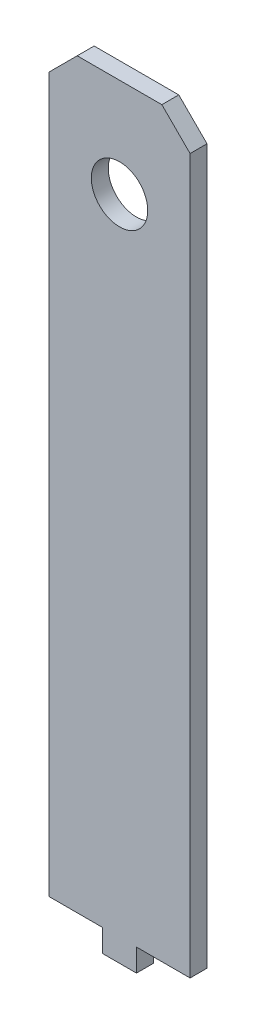
SolidWorks part; units mm, degrees
ref_plane "Front Plane" through (0, 0, 0) normal (0, 0, 1) x (1, 0, 0)
ref_plane "Top Plane" through (0, 0, 0) normal (0, 1, 0) x (1, 0, 0)
ref_plane "Right Plane" through (0, 0, 0) normal (1, 0, 0) x (0, 0, -1)
sketch "Sketch1" plane through (0, 0, 0) normal (0, 0, 1) x (1, 0, 0)
  line L2 (-12.5, 0) -> (-12.5, 135.5)
  line L3 (-12.5, 135.5) -> (12.5, 135.5)
  line L4 (12.5, 0) -> (12.5, 135.5)
  line L9 (12.5, 0) -> (-12.5, 0)
  dimension "D1" = 135.5
  dimension "D2" = 25
extrude "Boss-Extrude1" add sketch "Sketch1" along normal mid plane 3
sketch "Sketch2" plane through (0, 0, 1.5) normal (0, 0, 1) x (1, 0, 0)
  line L0 (0, 118) -> (0, 135.5) construction
  line L1 (12.5, 135.5) -> (-12.5, 135.5) construction
  circle A0 centre (0, 118) radius 5
  dimension "D1" = 10
  dimension "D2" = 17.5
extrude "Cut-Extrude1" cut sketch "Sketch2" against normal through all
chamfer "Chamfer1" distance 5 angle 45 2 edges at (12.5, 135.5, 0) (-12.5, 135.5, 0)
sketch "Sketch3" plane through (0, 0, 1.5) normal (0, 0, 1) x (1, 0, 0)
  line L1 (-12.5, 0) -> (-3, 0)
  line L2 (-12.5, 0) -> (-12.5, 4)
  line L3 (-12.5, 4) -> (-3, 4)
  line L4 (-3, 0) -> (-3, 4)
  line L5 (12.5, 0) -> (3, 0)
  line L6 (12.5, 0) -> (12.5, 4)
  line L7 (12.5, 4) -> (3, 4)
  line L8 (3, 0) -> (3, 4)
  dimension "D1" = 4
  dimension "D2" = 6
extrude "Cut-Extrude2" cut sketch "Sketch3" against normal through all
